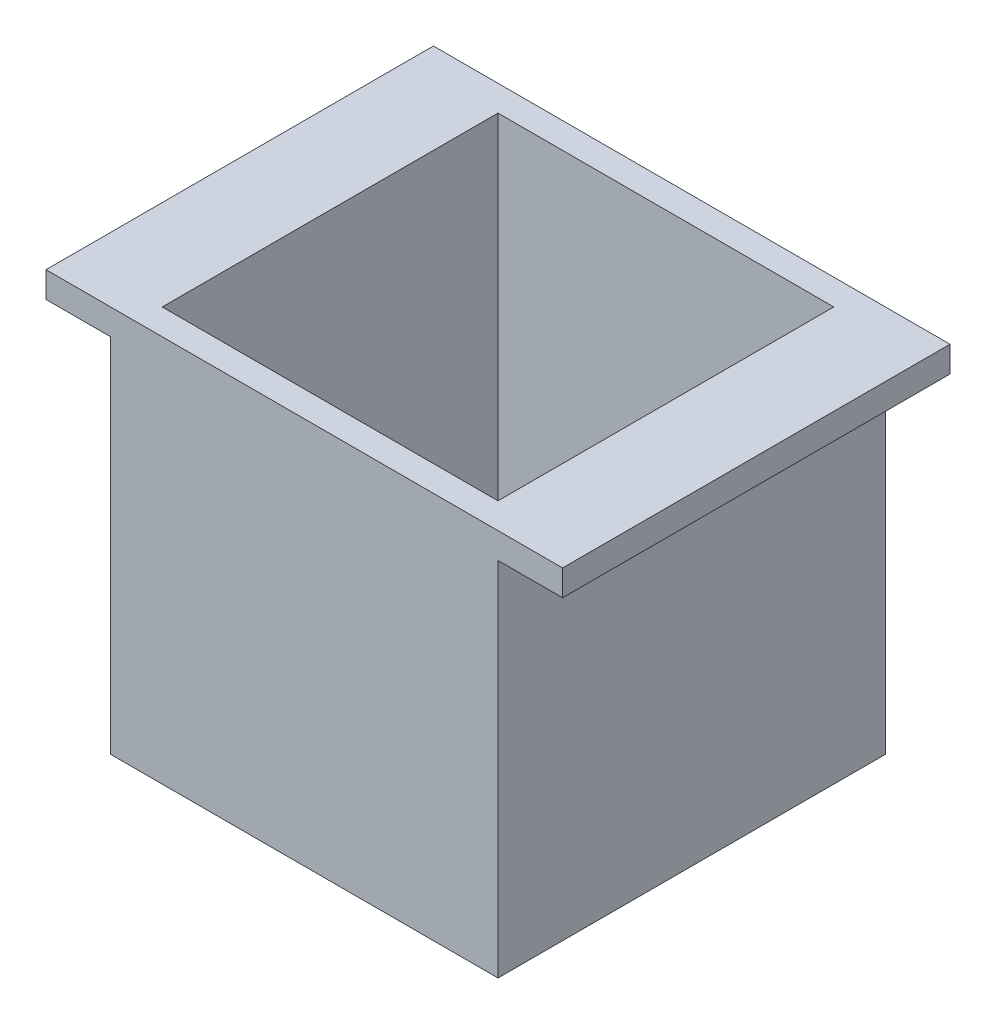
SolidWorks part; units mm, degrees
ref_plane "Přední rovina" through (0, 0, 0) normal (0, 0, 1) x (1, 0, 0)
ref_plane "Horní rovina" through (0, 0, 0) normal (0, 1, 0) x (1, 0, 0)
ref_plane "Pravá rovina" through (0, 0, 0) normal (1, 0, 0) x (0, 0, -1)
sketch "Skica1" plane through (0, 0, 0) normal (0, 0, 1) x (1, 0, 0)
  line L0 (0, 0) -> (0, 28)
  line L1 (0, 28) -> (-5, 28)
  line L2 (-5, 28) -> (-5, 30)
  line L3 (-5, 30) -> (35, 30)
  line L4 (35, 30) -> (35, 28)
  line L5 (35, 28) -> (30, 28)
  line L6 (30, 28) -> (30, 0)
  line L7 (30, 0) -> (0, 0)
  dimension "D1" = 30
  dimension "D2" = 30
  dimension "D3" = 2
  dimension "D4" = 5
extrude "Přidat vysunutím1" add sketch "Skica1" along normal blind 30
sketch "Skica2" plane through (0, 30, 0) normal (0, 1, 0) x (1, 0, 0)
  line L0 (35, -30) -> (-5, -30) construction
  line L1 (2, -28) -> (28, -28)
  line L2 (2, -28) -> (2, -2)
  line L3 (2, -2) -> (28, -2)
  line L4 (28, -28) -> (28, -2)
  line L5 (35, 0) -> (-5, 0) construction
  line L6 (15, 0) -> (15, -56) construction
  point P10 (15, -28)
  dimension "D1" = 2
  dimension "D2" = 2
  dimension "D3" = 26
extrude "Odebrat vysunutím1" cut sketch "Skica2" against normal blind 28
